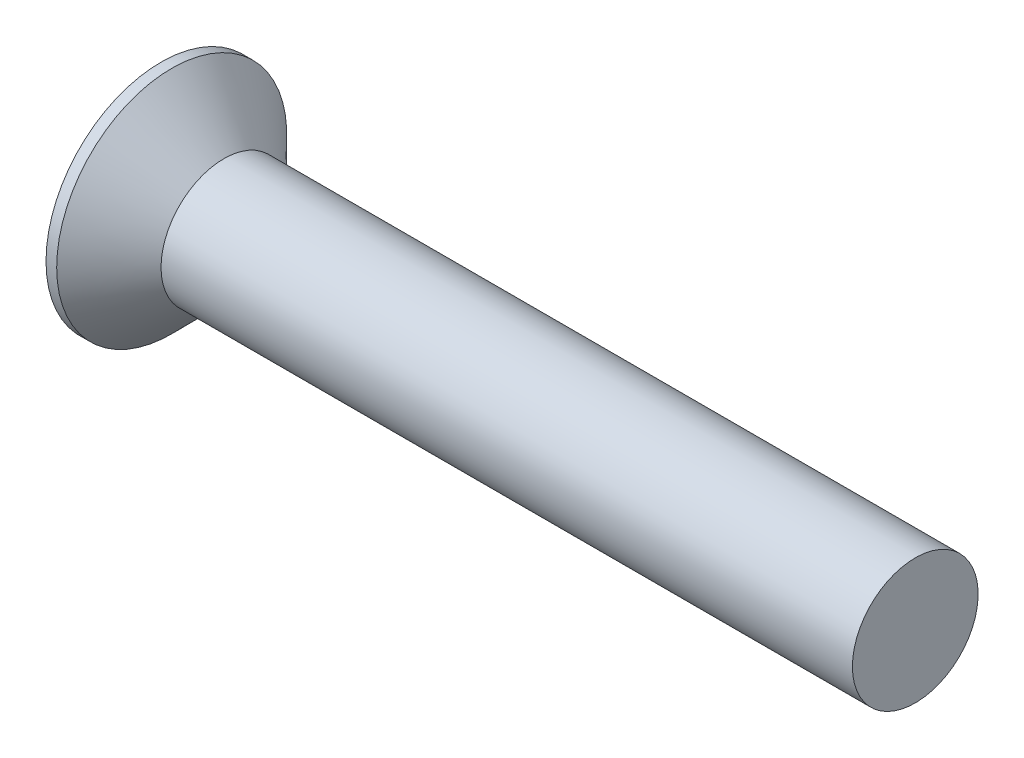
SolidWorks part; units mm, degrees
revolve "Base-Revolve" add sketch "BodySke" angle 360 about L5
sketch "BodySke" plane through (0, 0, 0) normal (0, 0, 1) x (1, 0, 0)
  line L0 (0, 0) -> (0, 9.15)
  line L1 (0, 9.15) -> (0.85, 9.15)
  line L2 (5, 5) -> (60, 5)
  line L3 (60, 5) -> (60, 0)
  line L4 (60, 0) -> (0, 0)
  line L5 (-6.35, 0) -> (82.55, 0) construction
  line L6 (5, -5) -> (60, -5) construction
  line L7 (0.85, -9.15) -> (5, -5) construction
  line L8 (0.85, 9.15) -> (5, 5)
  line L9 (0, -9.15) -> (0.85, -9.15) construction
  line L10 (6.5, 6.5875) -> (6.5, -2.9375) construction
  line L11 (0, 6.35) -> (0, -3.175) construction
  dimension "Diameter" = 10
  dimension "Length" = 60
  dimension "Head_ht" = 5
  dimension "Head_dia" = 18.3
  dimension "Head_ang" = 90
  dimension "D6" = 0.85
  dimension "Advance" = 1.5
  dimension "Thread_nom" = 60
cosmetic thread "ThreadCosmetic" parameters "Thread_length"=53.5, "Thread_minor"=8.344
extrude "Slot" [suppressed] cut sketch "Sketch2" against normal blind 2.6
sketch "Sketch2" plane through (0, 0, 0) normal (-1, 0, 0) x (0, 0, 1)
  line L0 (-9.15, -1.4) -> (9.15, -1.4)
  line L1 (-9.15, -1.4) -> (-9.15, 1.4)
  line L2 (9.15, 1.4) -> (-9.15, 1.4)
  line L3 (9.15, 1.4) -> (9.15, -1.4)
  dimension "Slot_width" = 2.8
  dimension "D1" = 1.4
  dimension "D2" = 18.3
  dimension "D3" = 9.15
ref_plane "Plane1" through (0, 0, 0) normal (0, 0, 1) x (1, 0, 0)
ref_plane "Plane2" through (0, 0, 0) normal (0, 1, 0) x (1, 0, 0)
ref_plane "Plane3" through (0, 0, 0) normal (1, 0, 0) x (0, 0, -1)
sketch "Sketch3" plane through (0, 0, 0) normal (-1, 0, 0) x (0, 0, 1)
  line L0 (-0.99, 4.94) -> (0.99, 4.94)
  line L1 (0.99, 4.94) -> (0.99, -4.94)
  line L2 (0.99, -4.94) -> (-0.99, -4.94)
  line L3 (-0.99, -4.94) -> (-0.99, 4.94)
  dimension "Cross_dia" = 9.88
  dimension "Cross_width" = 1.98
  dimension "D1" = 4.94
  dimension "D2" = 0.99
ref_plane "Plane4" through (5.98, 0, 0) normal (-1, 0, 0) x (0, 0, 1)
sketch "Sketch4" plane through (5.98, 0, 0) normal (-1, 0, 0) x (0, 0, 1)
  line L0 (-0.495, 0.495) -> (0.495, 0.495)
  line L3 (0.495, 0.495) -> (0.495, -0.495)
  line L4 (0.495, -0.495) -> (-0.495, -0.495)
  line L5 (-0.495, -0.495) -> (-0.495, 0.495)
  dimension "D2" = 0.99
  dimension "D1" = 0.99
  dimension "D3" = 0.495
  dimension "D4" = 0.495
loft "Cross" cut profiles "Sketch3", "Sketch4"
pattern_circular "CirPattern1" count 2 every 90 about axis through (0, 0, 0) along (1, 0, 0) of "Cross"
sketch "ThdSchSke" plane through (0, 0, 0) normal (0, 0, 1) x (1, 0, 0)
  line L0 (6.5, -4.172) -> (5.9202, -5)
  line L1 (6.5, -4.172) -> (7.0798, -5)
  line L2 (7.0798, -5) -> (7.0798, -6.25)
  line L3 (-3.175, 0) -> (5.1513, 0) construction
  line L5 (7.0798, -6.25) -> (5.9202, -6.25)
  line L6 (5.9202, -6.25) -> (5.9202, -5)
  line L7 (0, 9.15) -> (0, -9.15) construction
  dimension "Diameter" = 10
  dimension "Thread_minor" = 8.344
  dimension "Start" = 6.5
revolve "ThreadSchematic" [suppressed] cut sketch "ThdSchSke" angle 360 about L3
pattern_linear "ThdSchPat" [suppressed]
equation "\"D1@Sketch3\" = \"Cross_dia@Sketch3\" / 2"
equation "\"D2@Sketch3\" = \"Cross_width@Sketch3\" / 2"
equation "\"D1@Sketch4\" = \"Cross_width@Sketch3\" *.5"
equation "\"D2@Sketch4\" = \"D1@Sketch4\""
equation "\"D4@Sketch4\" = \"D2@Sketch4\" / 2"
equation "\"D3@Sketch4\" = \"D1@Sketch4\" / 2"
equation "\"D1@Sketch2\" = \"Slot_width@Sketch2\" / 2"
equation "\"D2@Sketch2\" = \"Head_dia@BodySke\""
equation "\"D3@Sketch2\" = \"D2@Sketch2\" / 2"
equation "\"Thread_length@ThreadCosmetic\" = ((sgn( (\"Length@BodySke\" - \"Advance@BodySke\" - \"Head_ht@BodySke\" ) - \"Thread_nom@BodySke\" )-1)*( (\"Length@BodySke\" - \"Advance@BodySke\" - \"Head_ht@BodySke\" ) - \"Thread_nom@BodySke\" ))/-2+ \"Thread_nom@BodySke\""
equation "\"Thread_minor@ThdSchSke\" = \"Thread_minor@ThreadCosmetic\""
equation "\"Diameter@ThdSchSke\" = \"Diameter@BodySke\""
equation "\"Overcut@ThdSchSke\" = \"Diameter@BodySke\" * 1.25"
equation "\"Start@ThdSchSke\" = 0.000001 + \"Length@BodySke\" - \"Thread_length@ThreadCosmetic\"  '---Countersunk---"
equation "\"Num_threads@ThdSchPat\" = int( \"Thread_length@ThreadCosmetic\" / \"Advance@BodySke\" + 0.999 )  + 1"
equation "\"Advance@ThdSchPat\" = \"Thread_length@ThreadCosmetic\" /  (\"Num_threads@ThdSchPat\" - 1) 'relax it"
